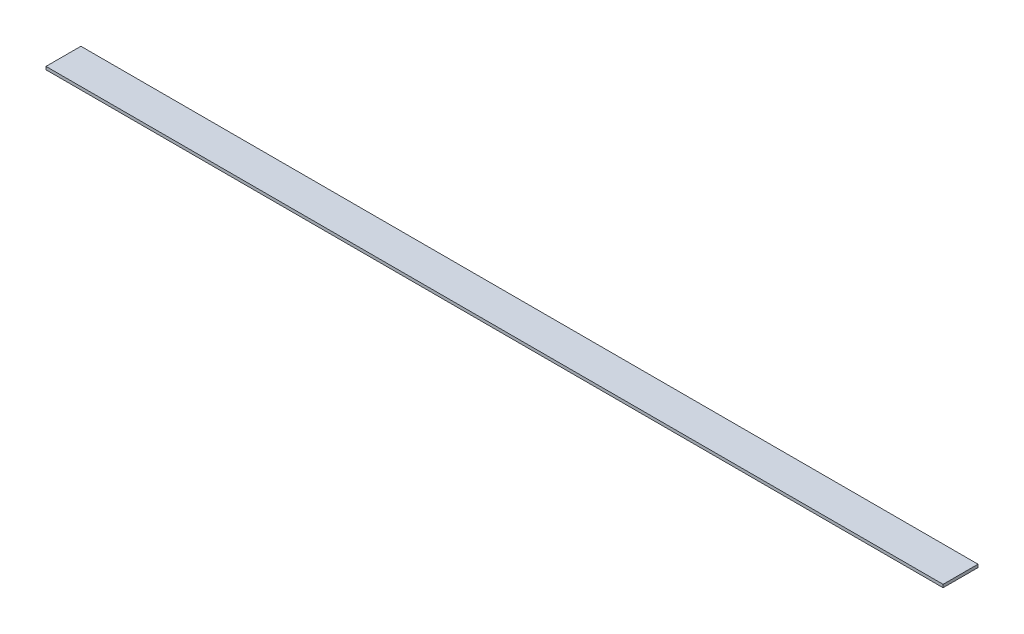
SolidWorks part; units mm, degrees
ref_plane "Front Plane" through (0, 0, 0) normal (0, 0, 1) x (1, 0, 0)
ref_plane "Top Plane" through (0, 0, 0) normal (0, 1, 0) x (1, 0, 0)
ref_plane "Right Plane" through (0, 0, 0) normal (1, 0, 0) x (0, 0, -1)
sketch "Sketch1" plane through (0, 0, 0) normal (0, 1, 0) x (1, 0, 0)
  line L1 (-450, -17.5) -> (450, -17.5)
  line L2 (-450, -17.5) -> (-450, 17.5)
  line L3 (-450, 17.5) -> (450, 17.5)
  line L4 (450, -17.5) -> (450, 17.5)
  line L5 (-450, -17.5) -> (450, 17.5) construction
  line L6 (-450, 17.5) -> (450, -17.5) construction
  point P0 (0, 0)
  dimension "D1" = 900
  dimension "D2" = 35
extrude "Boss-Extrude1" add sketch "Sketch1" along normal mid plane 3
